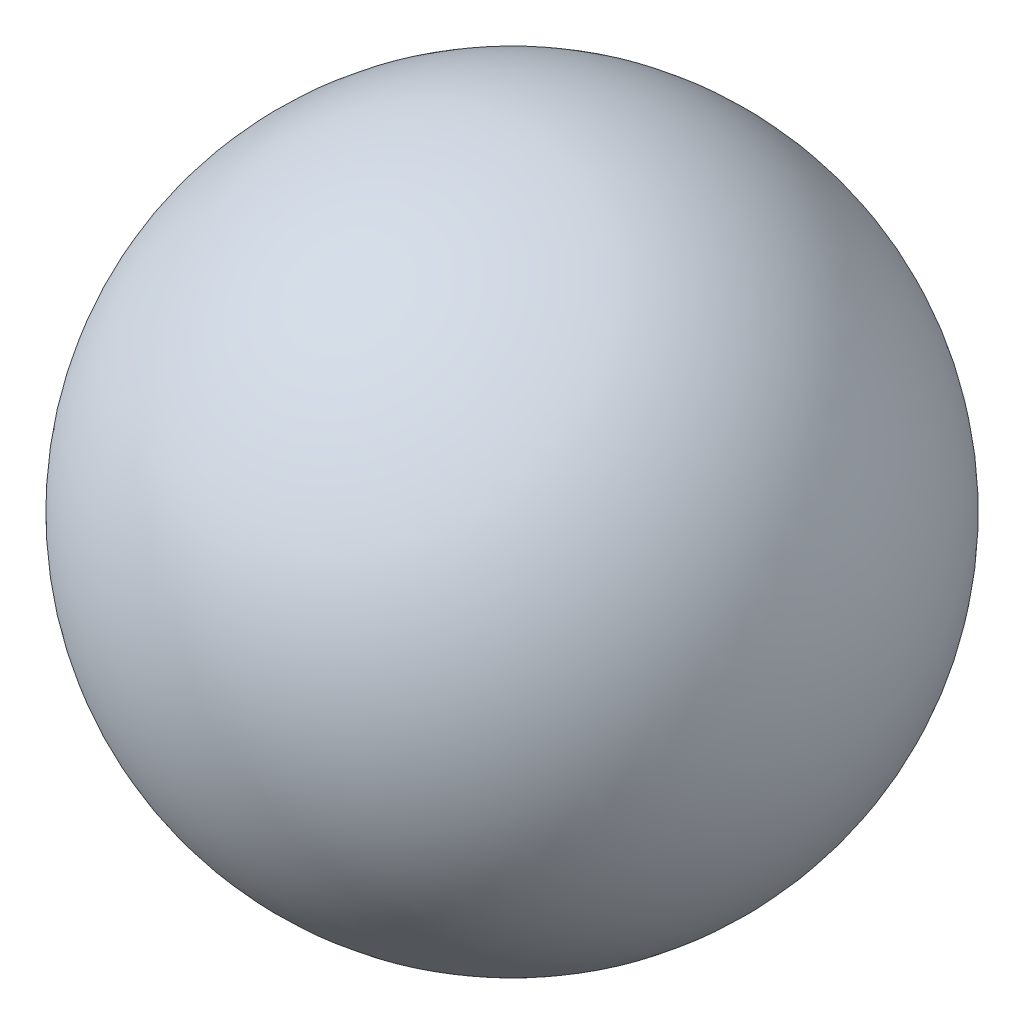
SolidWorks part; units mm, degrees
material "ABS PC"
ref_plane "Front Plane" through (0, 0, 0) normal (0, 0, 1) x (1, 0, 0)
ref_plane "Top Plane" through (0, 0, 0) normal (0, 1, 0) x (1, 0, 0)
ref_plane "Right Plane" through (0, 0, 0) normal (1, 0, 0) x (0, 0, -1)
sketch "Sketch1" plane through (0, 0, 0) normal (0, 0, 1) x (1, 0, 0)
  circle A0 centre (0, 0) radius 20
  dimension "D1" = 40
sketch "Sketch2" plane through (0, 0, 0) normal (0, 0, 1) x (1, 0, 0)
  line L0 (0, -22) -> (0, 22) construction
  line L1 (0, 20) -> (0, 19.475)
  line L2 (0, -19.475) -> (0, -20)
  arc A0 (0, 20) -> (0, -20) centre (0, 0) cw
  circle A1 centre (0, 0) radius 20 construction
  arc A2 (0, 19.475) -> (0, -19.475) centre (0, 0) cw
  dimension "D1" = 0.525
revolve "Revolve1" add sketch "Sketch2" angle 360 about L1
